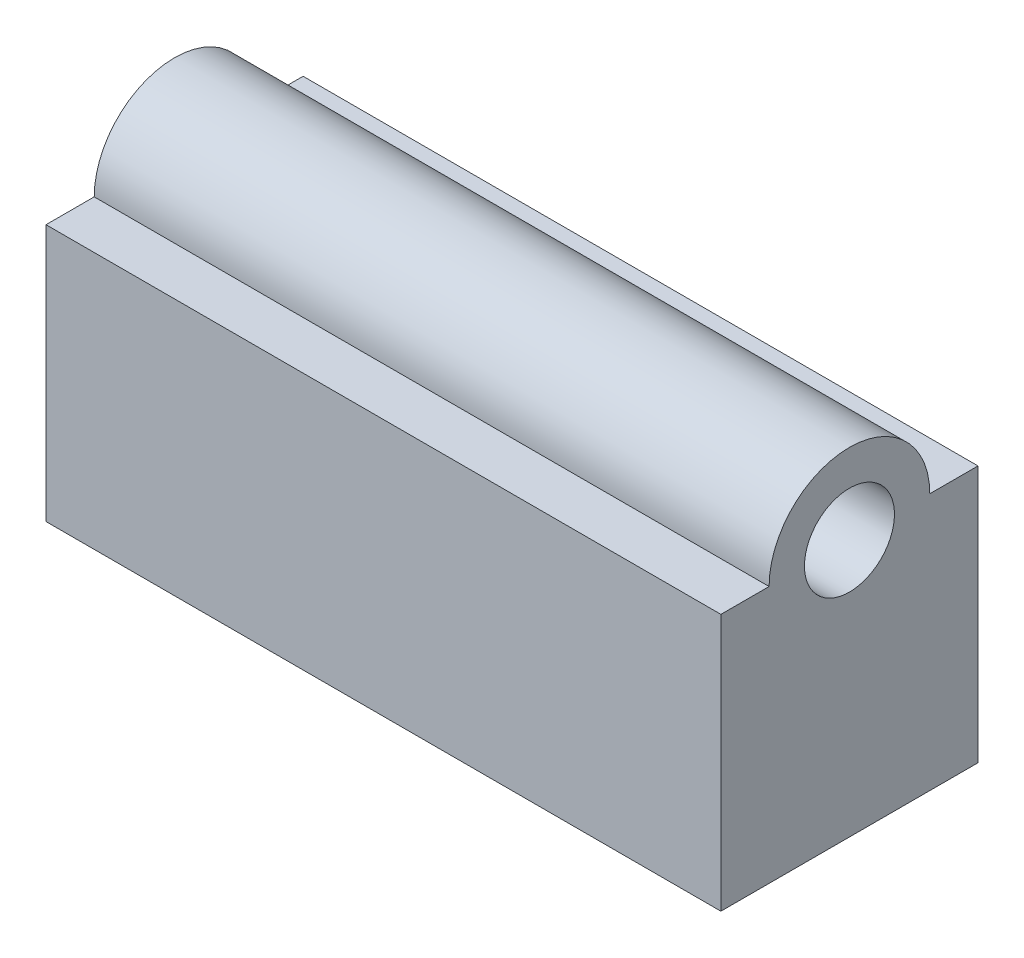
SolidWorks part; units mm, degrees
material "电池"
ref_plane "前视基准面" through (0, 0, 0) normal (0, 0, 1) x (1, 0, 0)
ref_plane "上视基准面" through (0, 0, 0) normal (0, 1, 0) x (1, 0, 0)
ref_plane "右视基准面" through (0, 0, 0) normal (1, 0, 0) x (0, 0, -1)
sketch "草图1" plane through (0, 0, 0) normal (0, 1, 0) x (1, 0, 0)
  line L1 (-105, 40) -> (105, 40)
  line L2 (-105, 40) -> (-105, -40)
  line L3 (-105, -40) -> (105, -40)
  line L4 (105, 40) -> (105, -40)
  line L5 (-105, 40) -> (105, -40) construction
  line L6 (-105, -40) -> (105, 40) construction
  point P0 (0, 0)
  dimension "D1" = 210
  dimension "D2" = 80
extrude "凸台-拉伸1" add sketch "草图1" along normal blind 50
sketch "草图2" plane through (-105, 0, 0) normal (-1, 0, 0) x (0, 0, 1)
  line L0 (-40, 50) -> (40, 50) construction
  line L1 (-40, 50) -> (40, 50)
  line L2 (25, 80) -> (40, 80)
  line L3 (-40, 50) -> (40, 50)
  line L4 (-40, 50) -> (-40, 80)
  line L5 (-40, 80) -> (-25, 80)
  line L6 (40, 50) -> (40, 80)
  arc A0 (25, 80) -> (-25, 80) centre (0, 80) ccw
  circle A1 centre (0, 80) radius 14
  point P5 (0, 50)
  line M9 (40, 50) -> (-40, 50)
  dimension "D2" = 28
  dimension "D3" = 50
  dimension "D1" = 30
extrude "凸台-拉伸2" add sketch "草图2" against normal up to surface (210 mm away) contours L2 A0 L5 L4 L6 A1 M9 up to face at (105, 25, 0)
